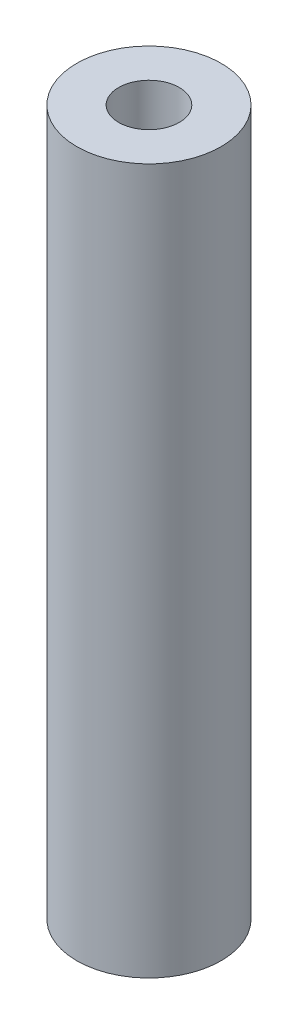
SolidWorks part; units mm, degrees
ref_plane "Front" through (0, 0, 0) normal (0, 0, 1) x (1, 0, 0)
ref_plane "Top" through (0, 0, 0) normal (0, 1, 0) x (1, 0, 0)
ref_plane "Right" through (0, 0, 0) normal (1, 0, 0) x (0, 0, -1)
sketch "Sketch1" plane through (0, 0, 0) normal (0, 1, 0) x (1, 0, 0)
  circle A0 centre (0, 0) radius 6.35
  circle A1 centre (0, 0) radius 2.665
  dimension "D1" = 12.7
  dimension "D2" = 5.33
extrude "Boss-Extrude1" add sketch "Sketch1" along normal blind 62
